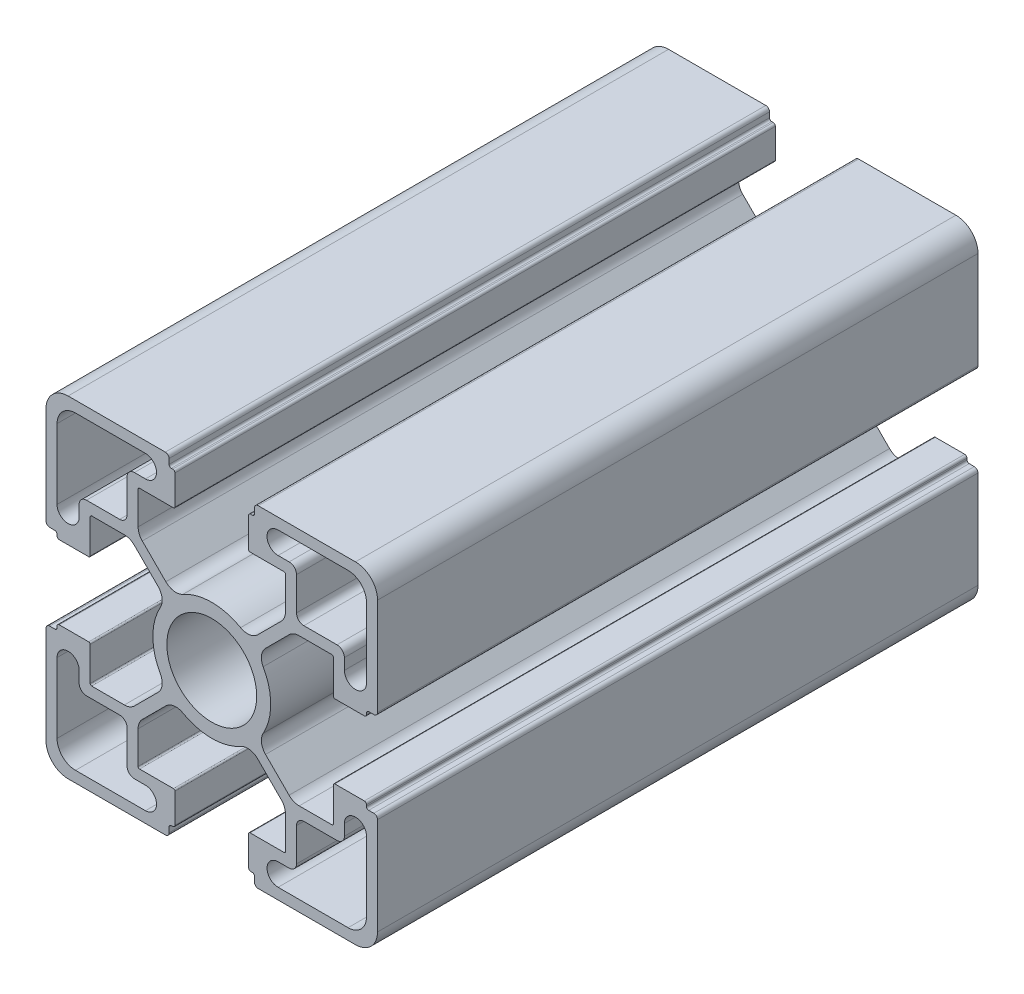
SolidWorks part; units mm, degrees
ref_plane "Front Plane" through (0, 0, 0) normal (0, 0, 1) x (1, 0, 0)
ref_plane "Top Plane" through (0, 0, 0) normal (0, 1, 0) x (1, 0, 0)
ref_plane "Right Plane" through (0, 0, 0) normal (1, 0, 0) x (0, 0, -1)
sketch "Sketch1" plane through (0, 0, 0) normal (0, 0, 1) x (1, 0, 0)
  line L3 (-22.5, 19.5) -> (-22.5, 6.3)
  line L4 (-20.7, 5) -> (-16.7, 5)
  line L5 (-16.5, 5.2) -> (-16.5, 9.8)
  line L6 (-16.3, 10) -> (-11.8642, 10)
  line L7 (-10.4924, 9.4318) -> (-7.2967, 6.236)
  line L8 (-21, 18.5) -> (-21, 9)
  line L9 (-16.5, 5) -> (-16.5, 10) construction
  line L10 (-18, 9) -> (-18, 10.5)
  line L11 (-17, 11.5) -> (-12.5, 11.5)
  line L12 (-22, 5.8) -> (-21.3, 5.8)
  line L13 (-21, 5.5) -> (-21, 5.3)
  line L14 (-21, 22.5) -> (-21, 6.5) construction
  line L15 (-18, 11.5) -> (-10.4393, 11.5) construction
  line L16 (-10.4393, 11.5) -> (-5.1016, 6.1623) construction
  line L17 (-18, 6.5) -> (-18, 11.5) construction
  line L18 (-22.5, 22.5) -> (-22.5, 5) construction
  line L19 (-22.5, 5) -> (-16.5, 5) construction
  line L20 (-21, 6.5) -> (-18, 6.5) construction
  line L21 (-16.5, 10) -> (-11.0607, 10) construction
  line L22 (-11.0607, 10) -> (-6.1623, 5.1016) construction
  line L23 (-5.5, 21) -> (-5.3, 21)
  line L24 (-5.8, 22) -> (-5.8, 21.3)
  line L25 (-11.5, 17) -> (-11.5, 12.5)
  line L26 (-9, 18) -> (-10.5, 18)
  line L27 (-18.5, 21) -> (-9, 21)
  line L28 (-9.4318, 10.4924) -> (-6.236, 7.2967)
  line L29 (-10, 16.3) -> (-10, 11.8642)
  line L30 (-5.2, 16.5) -> (-9.8, 16.5)
  line L31 (-5, 20.7) -> (-5, 16.7)
  line L32 (-19.5, 22.5) -> (-6.3, 22.5)
  line L33 (19.5, 22.5) -> (6.3, 22.5)
  line L34 (5, 20.7) -> (5, 16.7)
  line L35 (5.2, 16.5) -> (9.8, 16.5)
  line L36 (10, 16.3) -> (10, 11.8642)
  line L37 (9.4318, 10.4924) -> (6.236, 7.2967)
  line L38 (18.5, 21) -> (9, 21)
  line L39 (9, 18) -> (10.5, 18)
  line L40 (11.5, 17) -> (11.5, 12.5)
  line L41 (5.8, 22) -> (5.8, 21.3)
  line L42 (5.5, 21) -> (5.3, 21)
  line L43 (21, 5.5) -> (21, 5.3)
  line L44 (22, 5.8) -> (21.3, 5.8)
  line L45 (17, 11.5) -> (12.5, 11.5)
  line L46 (18, 9) -> (18, 10.5)
  line L47 (21, 18.5) -> (21, 9)
  line L48 (10.4924, 9.4318) -> (7.2967, 6.236)
  line L49 (16.3, 10) -> (11.8642, 10)
  line L50 (16.5, 5.2) -> (16.5, 9.8)
  line L51 (20.7, 5) -> (16.7, 5)
  line L52 (22.5, 19.5) -> (22.5, 6.3)
  line L53 (22.5, -19.5) -> (22.5, -6.3)
  line L54 (20.7, -5) -> (16.7, -5)
  line L55 (16.5, -5.2) -> (16.5, -9.8)
  line L56 (16.3, -10) -> (11.8642, -10)
  line L57 (10.4924, -9.4318) -> (7.2967, -6.236)
  line L58 (21, -18.5) -> (21, -9)
  line L59 (18, -9) -> (18, -10.5)
  line L60 (17, -11.5) -> (12.5, -11.5)
  line L61 (22, -5.8) -> (21.3, -5.8)
  line L62 (21, -5.5) -> (21, -5.3)
  line L63 (5.5, -21) -> (5.3, -21)
  line L64 (5.8, -22) -> (5.8, -21.3)
  line L65 (11.5, -17) -> (11.5, -12.5)
  line L66 (9, -18) -> (10.5, -18)
  line L67 (18.5, -21) -> (9, -21)
  line L68 (9.4318, -10.4924) -> (6.236, -7.2967)
  line L69 (10, -16.3) -> (10, -11.8642)
  line L70 (5.2, -16.5) -> (9.8, -16.5)
  line L71 (5, -20.7) -> (5, -16.7)
  line L72 (19.5, -22.5) -> (6.3, -22.5)
  line L73 (-19.5, -22.5) -> (-6.3, -22.5)
  line L74 (-5, -20.7) -> (-5, -16.7)
  line L75 (-5.2, -16.5) -> (-9.8, -16.5)
  line L76 (-10, -16.3) -> (-10, -11.8642)
  line L77 (-9.4318, -10.4924) -> (-6.236, -7.2967)
  line L78 (-18.5, -21) -> (-9, -21)
  line L79 (-9, -18) -> (-10.5, -18)
  line L80 (-11.5, -17) -> (-11.5, -12.5)
  line L81 (-5.8, -22) -> (-5.8, -21.3)
  line L82 (-5.5, -21) -> (-5.3, -21)
  line L83 (-21, -5.5) -> (-21, -5.3)
  line L84 (-22, -5.8) -> (-21.3, -5.8)
  line L85 (-17, -11.5) -> (-12.5, -11.5)
  line L86 (-18, -9) -> (-18, -10.5)
  line L87 (-21, -18.5) -> (-21, -9)
  line L88 (-10.4924, -9.4318) -> (-7.2967, -6.236)
  line L89 (-16.3, -10) -> (-11.8642, -10)
  line L90 (-16.5, -5.2) -> (-16.5, -9.8)
  line L91 (-20.7, -5) -> (-16.7, -5)
  line L92 (-22.5, -19.5) -> (-22.5, -6.3)
  arc A0 (0, 6.1) -> (-6.1, 0) centre (0, 0) ccw
  arc A1 (-6.9766, 3.9149) -> (-8, 0) centre (0, 0) ccw
  arc A2 (-21, 9) -> (-18, 9) centre (-19.5, 9) ccw
  arc A3 (-22, 5.8) -> (-22.5, 6.3) centre (-22, 6.3) cw
  arc A4 (-21, 5.3) -> (-20.7, 5) centre (-20.7, 5.3) ccw
  arc A5 (-21.3, 5.8) -> (-21, 5.5) centre (-21.3, 5.5) cw
  arc A6 (-16.7, 5) -> (-16.5, 5.2) centre (-16.7, 5.2) ccw
  arc A7 (-16.5, 9.8) -> (-16.3, 10) centre (-16.3, 9.8) cw
  arc A8 (-7.2967, 6.236) -> (-6.9766, 3.9149) centre (-8.6685, 4.8643) cw
  arc A9 (-11.8642, 10) -> (-10.4924, 9.4318) centre (-11.8642, 8.06) cw
  arc A10 (-18, 10.5) -> (-17, 11.5) centre (-17, 10.5) cw
  arc A11 (-10.5, 18) -> (-11.5, 17) centre (-10.5, 17) ccw
  arc A12 (-10, 11.8642) -> (-9.4318, 10.4924) centre (-8.06, 11.8642) ccw
  arc A13 (-6.236, 7.2967) -> (-3.9149, 6.9766) centre (-4.8643, 8.6685) ccw
  arc A14 (-9.8, 16.5) -> (-10, 16.3) centre (-9.8, 16.3) ccw
  arc A15 (-5, 16.7) -> (-5.2, 16.5) centre (-5.2, 16.7) cw
  arc A16 (-5.8, 21.3) -> (-5.5, 21) centre (-5.5, 21.3) ccw
  arc A17 (-5.3, 21) -> (-5, 20.7) centre (-5.3, 20.7) cw
  arc A18 (-5.8, 22) -> (-6.3, 22.5) centre (-6.3, 22) ccw
  arc A19 (-9, 21) -> (-9, 18) centre (-9, 19.5) cw
  arc A20 (-3.9149, 6.9766) -> (0, 8) centre (0, 0) cw
  arc A21 (-21, 18.5) -> (-18.5, 21) centre (-18.5, 18.5) cw
  arc A22 (-22.5, 19.5) -> (-19.5, 22.5) centre (-19.5, 19.5) cw
  arc A23 (-12.5, 11.5) -> (-11.5, 12.5) centre (-12.5, 12.5) ccw
  arc A24 (6.1, 0) -> (0, 6.1) centre (0, 0) ccw
  arc A25 (3.9149, 6.9766) -> (0, 8) centre (0, 0) ccw
  arc A26 (9, 21) -> (9, 18) centre (9, 19.5) ccw
  arc A27 (5.8, 22) -> (6.3, 22.5) centre (6.3, 22) cw
  arc A28 (5.3, 21) -> (5, 20.7) centre (5.3, 20.7) ccw
  arc A29 (5.8, 21.3) -> (5.5, 21) centre (5.5, 21.3) cw
  arc A30 (5, 16.7) -> (5.2, 16.5) centre (5.2, 16.7) ccw
  arc A31 (9.8, 16.5) -> (10, 16.3) centre (9.8, 16.3) cw
  arc A32 (6.236, 7.2967) -> (3.9149, 6.9766) centre (4.8643, 8.6685) cw
  arc A33 (10, 11.8642) -> (9.4318, 10.4924) centre (8.06, 11.8642) cw
  arc A34 (10.5, 18) -> (11.5, 17) centre (10.5, 17) cw
  arc A35 (18, 10.5) -> (17, 11.5) centre (17, 10.5) ccw
  arc A36 (11.8642, 10) -> (10.4924, 9.4318) centre (11.8642, 8.06) ccw
  arc A37 (7.2967, 6.236) -> (6.9766, 3.9149) centre (8.6685, 4.8643) ccw
  arc A38 (16.5, 9.8) -> (16.3, 10) centre (16.3, 9.8) ccw
  arc A39 (16.7, 5) -> (16.5, 5.2) centre (16.7, 5.2) cw
  arc A40 (21.3, 5.8) -> (21, 5.5) centre (21.3, 5.5) ccw
  arc A41 (21, 5.3) -> (20.7, 5) centre (20.7, 5.3) cw
  arc A42 (22, 5.8) -> (22.5, 6.3) centre (22, 6.3) ccw
  arc A43 (21, 9) -> (18, 9) centre (19.5, 9) cw
  arc A44 (6.9766, 3.9149) -> (8, 0) centre (0, 0) cw
  arc A45 (18.5, 21) -> (21, 18.5) centre (18.5, 18.5) cw
  arc A46 (19.5, 22.5) -> (22.5, 19.5) centre (19.5, 19.5) cw
  arc A47 (11.5, 12.5) -> (12.5, 11.5) centre (12.5, 12.5) ccw
  arc A48 (0, -6.1) -> (6.1, 0) centre (0, 0) ccw
  arc A49 (6.9766, -3.9149) -> (8, 0) centre (0, 0) ccw
  arc A50 (21, -9) -> (18, -9) centre (19.5, -9) ccw
  arc A51 (22, -5.8) -> (22.5, -6.3) centre (22, -6.3) cw
  arc A52 (21, -5.3) -> (20.7, -5) centre (20.7, -5.3) ccw
  arc A53 (21.3, -5.8) -> (21, -5.5) centre (21.3, -5.5) cw
  arc A54 (16.7, -5) -> (16.5, -5.2) centre (16.7, -5.2) ccw
  arc A55 (16.5, -9.8) -> (16.3, -10) centre (16.3, -9.8) cw
  arc A56 (7.2967, -6.236) -> (6.9766, -3.9149) centre (8.6685, -4.8643) cw
  arc A57 (11.8642, -10) -> (10.4924, -9.4318) centre (11.8642, -8.06) cw
  arc A58 (18, -10.5) -> (17, -11.5) centre (17, -10.5) cw
  arc A59 (10.5, -18) -> (11.5, -17) centre (10.5, -17) ccw
  arc A60 (10, -11.8642) -> (9.4318, -10.4924) centre (8.06, -11.8642) ccw
  arc A61 (6.236, -7.2967) -> (3.9149, -6.9766) centre (4.8643, -8.6685) ccw
  arc A62 (9.8, -16.5) -> (10, -16.3) centre (9.8, -16.3) ccw
  arc A63 (5, -16.7) -> (5.2, -16.5) centre (5.2, -16.7) cw
  arc A64 (5.8, -21.3) -> (5.5, -21) centre (5.5, -21.3) ccw
  arc A65 (5.3, -21) -> (5, -20.7) centre (5.3, -20.7) cw
  arc A66 (5.8, -22) -> (6.3, -22.5) centre (6.3, -22) ccw
  arc A67 (9, -21) -> (9, -18) centre (9, -19.5) cw
  arc A68 (3.9149, -6.9766) -> (0, -8) centre (0, 0) cw
  arc A69 (21, -18.5) -> (18.5, -21) centre (18.5, -18.5) cw
  arc A70 (22.5, -19.5) -> (19.5, -22.5) centre (19.5, -19.5) cw
  arc A71 (12.5, -11.5) -> (11.5, -12.5) centre (12.5, -12.5) ccw
  arc A72 (-6.1, 0) -> (0, -6.1) centre (0, 0) ccw
  arc A73 (-3.9149, -6.9766) -> (0, -8) centre (0, 0) ccw
  arc A74 (-9, -21) -> (-9, -18) centre (-9, -19.5) ccw
  arc A75 (-5.8, -22) -> (-6.3, -22.5) centre (-6.3, -22) cw
  arc A76 (-5.3, -21) -> (-5, -20.7) centre (-5.3, -20.7) ccw
  arc A77 (-5.8, -21.3) -> (-5.5, -21) centre (-5.5, -21.3) cw
  arc A78 (-5, -16.7) -> (-5.2, -16.5) centre (-5.2, -16.7) ccw
  arc A79 (-9.8, -16.5) -> (-10, -16.3) centre (-9.8, -16.3) cw
  arc A80 (-6.236, -7.2967) -> (-3.9149, -6.9766) centre (-4.8643, -8.6685) cw
  arc A81 (-10, -11.8642) -> (-9.4318, -10.4924) centre (-8.06, -11.8642) cw
  arc A82 (-10.5, -18) -> (-11.5, -17) centre (-10.5, -17) cw
  arc A83 (-18, -10.5) -> (-17, -11.5) centre (-17, -10.5) ccw
  arc A84 (-11.8642, -10) -> (-10.4924, -9.4318) centre (-11.8642, -8.06) ccw
  arc A85 (-7.2967, -6.236) -> (-6.9766, -3.9149) centre (-8.6685, -4.8643) ccw
  arc A86 (-16.5, -9.8) -> (-16.3, -10) centre (-16.3, -9.8) ccw
  arc A87 (-16.7, -5) -> (-16.5, -5.2) centre (-16.7, -5.2) cw
  arc A88 (-21.3, -5.8) -> (-21, -5.5) centre (-21.3, -5.5) ccw
  arc A89 (-21, -5.3) -> (-20.7, -5) centre (-20.7, -5.3) cw
  arc A90 (-22, -5.8) -> (-22.5, -6.3) centre (-22, -6.3) ccw
  arc A91 (-21, -9) -> (-18, -9) centre (-19.5, -9) cw
  arc A92 (-6.9766, -3.9149) -> (-8, 0) centre (0, 0) cw
  arc A93 (-18.5, -21) -> (-21, -18.5) centre (-18.5, -18.5) cw
  arc A94 (-19.5, -22.5) -> (-22.5, -19.5) centre (-19.5, -19.5) cw
  arc A95 (-11.5, -12.5) -> (-12.5, -11.5) centre (-12.5, -12.5) ccw
  point P24 (-5.8, 21)
  point P32 (-22.5, 5.8)
  point P35 (-21, 5)
  point P38 (-21, 5.8)
  point P83 (-5, 21)
  point P84 (-5.8, 22.5)
  point P87 (-21, 21)
  point P93 (-11.5, 11.5)
  point P102 (21, 5.8)
  point P158 (21, 5)
  point P159 (22.5, 5.8)
  point P172 (5.8, -21)
  point P228 (5, -21)
  point P229 (5.8, -22.5)
  point P242 (-21, -5.8)
  point P298 (-21, -5)
  point P299 (-22.5, -5.8)
  dimension "D11" = 0.5
  dimension "D12" = 0.3
  dimension "D13" = 0.2
  dimension "D14" = 0.2
  dimension "D6" = 1.94
  dimension "D15" = 1
  dimension "D16" = 2.5
  dimension "D4" = 3
  dimension "D17" = 1
  dimension "D5" = 0.8
  dimension "D7" = 1.5
  dimension "D9" = 1.5
  dimension "D10" = 4
  dimension "D18" = 4
extrude "Boss-Extrude1" add sketch "Sketch1" along normal blind 81.4958
scale "Scale1" scale about centroid uniform scaling yes scale factor 0.564444
